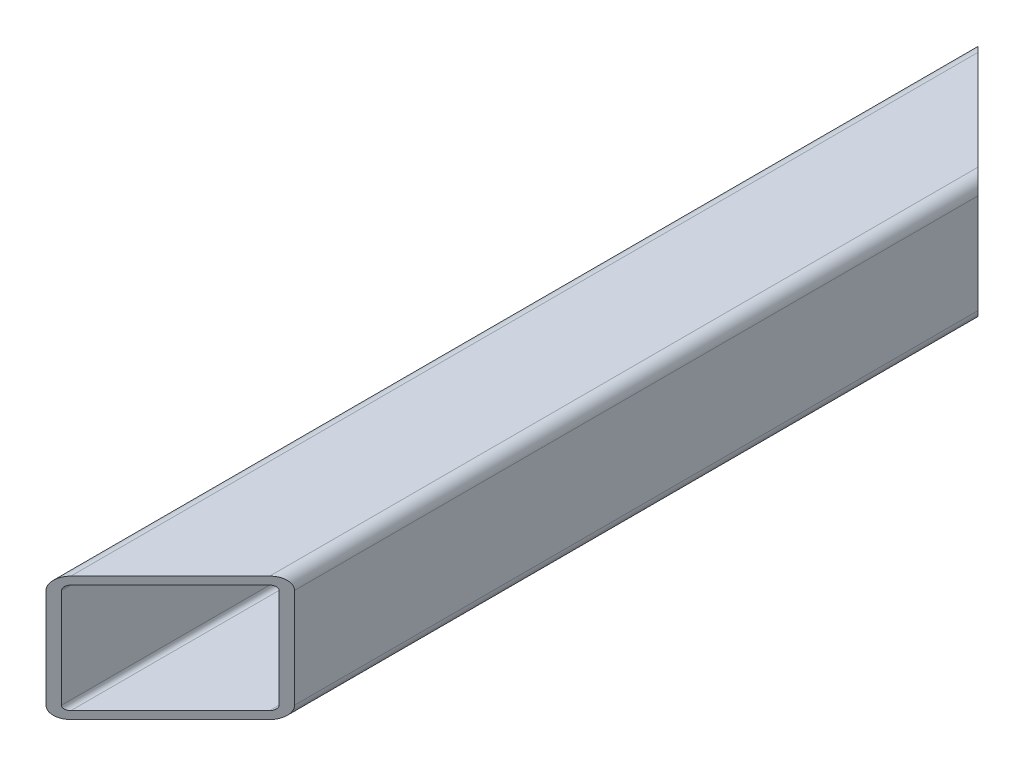
SolidWorks part; units mm, degrees
material "1.0037 (S235JR)"
ref_plane "Płaszczyzna przednia" through (0, 0, 0) normal (0, 0, 1) x (1, 0, 0)
ref_plane "Płaszczyzna górna" through (0, 0, 0) normal (0, 1, 0) x (1, 0, 0)
ref_plane "Płaszczyzna prawa" through (0, 0, 0) normal (1, 0, 0) x (0, 0, -1)
sketch "Szkic1" plane through (0, 0, 0) normal (0, 0, 1) x (1, 0, 0)
  line L0 (8, 75) -> (72, 75)
  line L1 (8, 0) -> (72, 0)
  line L2 (0, 8) -> (0, 72)
  line L3 (8, 80) -> (72, 80)
  line L4 (80, 8) -> (80, 72)
  line L5 (75, 8) -> (75, 72)
  line L6 (8, 5) -> (72, 5)
  line L7 (5, 8) -> (5, 72)
  arc A0 (80, 8) -> (72, 0) centre (72, 8) cw
  arc A1 (8, 0) -> (0, 8) centre (8, 8) cw
  arc A2 (80, 72) -> (72, 80) centre (72, 72) ccw
  arc A3 (8, 80) -> (0, 72) centre (8, 72) ccw
  arc A4 (75, 72) -> (72, 75) centre (72, 72) ccw
  arc A5 (75, 8) -> (72, 5) centre (72, 8) cw
  arc A6 (8, 5) -> (5, 8) centre (8, 8) cw
  arc A7 (8, 75) -> (5, 72) centre (8, 72) ccw
  dimension "D2" = 5
  dimension "D1" = 80
  dimension "D4" = 8
extrude "Dodanie-wyciągnięcie1" add sketch "Szkic1" against normal blind 600
sketch "Szkic2" plane through (0, 80, 0) normal (0, 1, 0) x (1, 0, 0)
  line L0 (0, 300) -> (80, 300) construction
  line L1 (0, 600) -> (0, 0) construction
  line L2 (80, 600) -> (80, 0) construction
  line L3 (0, 0) -> (80, 0)
  line L4 (80, 0) -> (80, 80)
  line L5 (80, 80) -> (0, 0)
  line L6 (80, 520) -> (0, 600)
  line L7 (80, 600) -> (80, 520)
  line L8 (0, 600) -> (80, 600)
extrude "Wytnij-wyciągnięcie1" cut sketch "Szkic2" against normal through all
